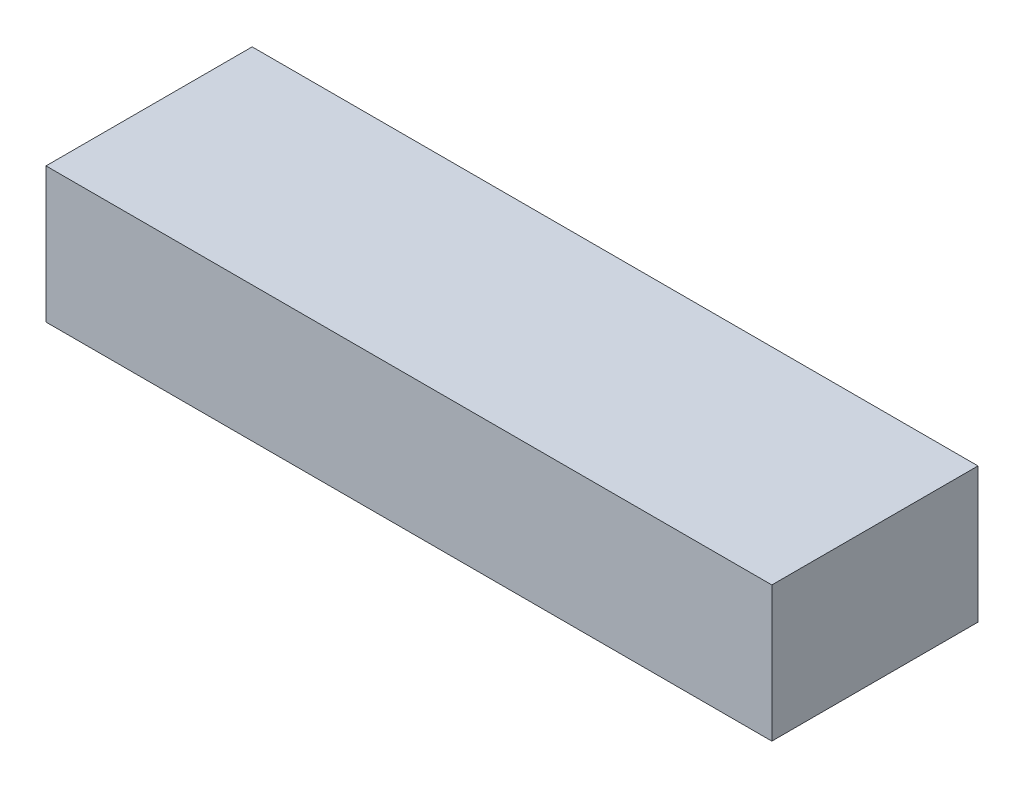
SolidWorks part; units mm, degrees
material "C (Graphite)"
ref_plane "Front Plane" through (0, 0, 0) normal (0, 0, 1) x (1, 0, 0)
ref_plane "Top Plane" through (0, 0, 0) normal (0, 1, 0) x (1, 0, 0)
ref_plane "Right Plane" through (0, 0, 0) normal (1, 0, 0) x (0, 0, -1)
sketch "Sketch1" plane through (0, 0, 0) normal (0, 1, 0) x (1, 0, 0)
  line L1 (-84.5, 24) -> (84.5, 24)
  line L2 (-84.5, 24) -> (-84.5, -24)
  line L3 (-84.5, -24) -> (84.5, -24)
  line L4 (84.5, 24) -> (84.5, -24)
  line L5 (-84.5, 24) -> (84.5, -24) construction
  line L6 (-84.5, -24) -> (84.5, 24) construction
  point P0 (0, 0)
extrude "Boss-Extrude1" add sketch "Sketch1" along normal blind 31.5
